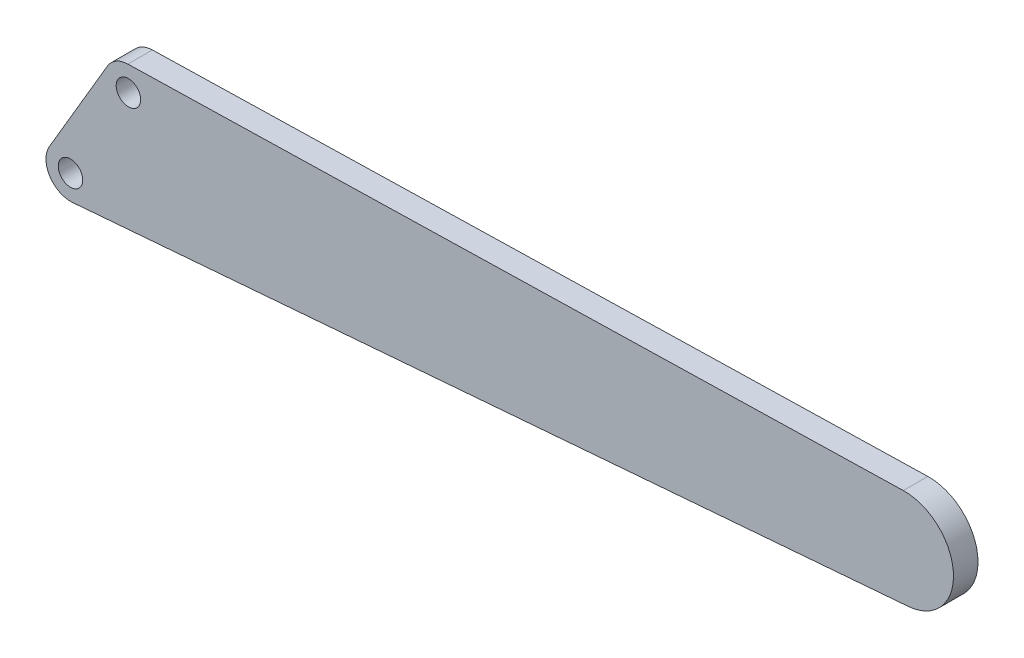
SolidWorks part; units mm, degrees
ref_plane "Front Plane" through (0, 0, 0) normal (0, 0, 1) x (1, 0, 0)
ref_plane "Top Plane" through (0, 0, 0) normal (0, 1, 0) x (1, 0, 0)
ref_plane "Right Plane" through (0, 0, 0) normal (1, 0, 0) x (0, 0, -1)
sketch "Sketch2" plane through (0, 0, 0) normal (0, 0, 1) x (1, 0, 0)
  line L0 (-7.0951, -12.069) -> (0, 0)
  line L1 (0, 0) -> (95, -0.7468)
  dimension "D1" = 95
  dimension "D2" = 14
  dimension "D3" = 120
sketch "Sketch3" plane through (0, 0, 0) normal (0, 0, 1) x (1, 0, 0)
  line L0 (-9.6813, -10.5486) -> (-2.5862, 1.5204)
  line L1 (-0.0712, 2.9992) -> (94.8577, 5.2515)
  line L2 (95.4869, -6.727) -> (-6.8516, -15.0591)
  circle A0 centre (-7.0951, -12.069) radius 1.5
  arc A1 (-9.6813, -10.5486) -> (-6.8516, -15.0591) centre (-7.0951, -12.069) ccw
  circle A2 centre (0, 0) radius 1.5
  arc A3 (-0.0712, 2.9992) -> (-2.5862, 1.5204) centre (0, 0) ccw
  arc A4 (95.4869, -6.727) -> (94.8577, 5.2515) centre (95, -0.7468) ccw
  dimension "D1" = 3
  dimension "D2" = 6
  dimension "D3" = 3
  dimension "D4" = 6
  dimension "D5" = 12
extrude "Boss-Extrude1" add sketch "Sketch3" along normal blind 3
